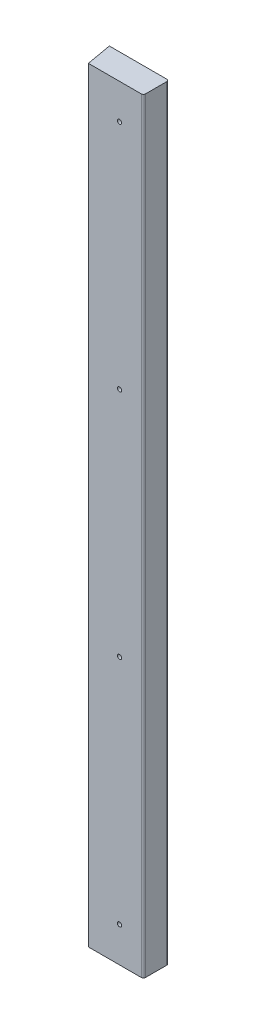
SolidWorks part; units mm, degrees
ref_plane "Front" through (0, 0, 0) normal (0, 0, 1) x (1, 0, 0)
ref_plane "Top" through (0, 0, 0) normal (0, 1, 0) x (1, 0, 0)
ref_plane "Right" through (0, 0, 0) normal (1, 0, 0) x (0, 0, -1)
sketch "Sketch1" plane through (0, 0, 0) normal (0, 1, 0) x (1, 0, 0)
  line L0 (-44.45, 19.05) -> (-37.7319, -19.05)
  line L1 (44.45, 19.05) -> (-44.45, 19.05)
  line L2 (44.45, 19.05) -> (44.45, -19.05)
  line L3 (44.45, -19.05) -> (-37.7319, -19.05)
  line L4 (-44.45, 19.05) -> (-44.45, -19.05) construction
  line L5 (44.45, 19.05) -> (-44.45, -19.05) construction
  line L6 (44.45, -19.05) -> (-44.45, 19.05) construction
  line L7 (-37.7319, -19.05) -> (-44.45, -19.05) construction
  point P0 (0, 0)
  dimension "D1" = 38.1
  dimension "D2" = 88.9
  dimension "D3" = 80
extrude "Boss-Extrude1" add sketch "Sketch1" along normal blind 1143
hole_wizard "1/4 (0.25) Diameter Hole1" positions "Sketch2" profile "Sketch3" hole size "1/4" standard "ANSI Inch"
sketch "Sketch2" plane through (0, 0, 19.05) normal (0, 0, -1) x (-1, 0, 0)
  line L0 (-44.45, 0) -> (44.45, 0) construction
  line L2 (37.7319, 1143) -> (37.7319, 0) construction
  point P0 (-8.8174, 52.3875)
  point P33 (-8.8174, 398.4625)
  point P34 (-8.8174, 744.5375)
  point P35 (-8.8174, 1090.6125)
  dimension "D1" = 52.3875
  dimension "D3" = 46.5494
  dimension "D2" = 4
sketch "Sketch3" plane through (8.8174, 52.3875, 19.05) normal (1, 0, 0) x (0, -1, 0)
  line L0 (0, 0) -> (0, 38.1)
  line L1 (0, 38.1) -> (3.175, 38.1)
  line L2 (3.175, 38.1) -> (3.175, 0)
  line L5 (3.175, 0) -> (0, 0)
  line L11 (0, -6.35) -> (0, 107.95) construction
  dimension "Thru Hole Dia." = 6.35
  dimension "Thru Hole Depth" = 38.1
fillet "Fillet2" radius 3.175
